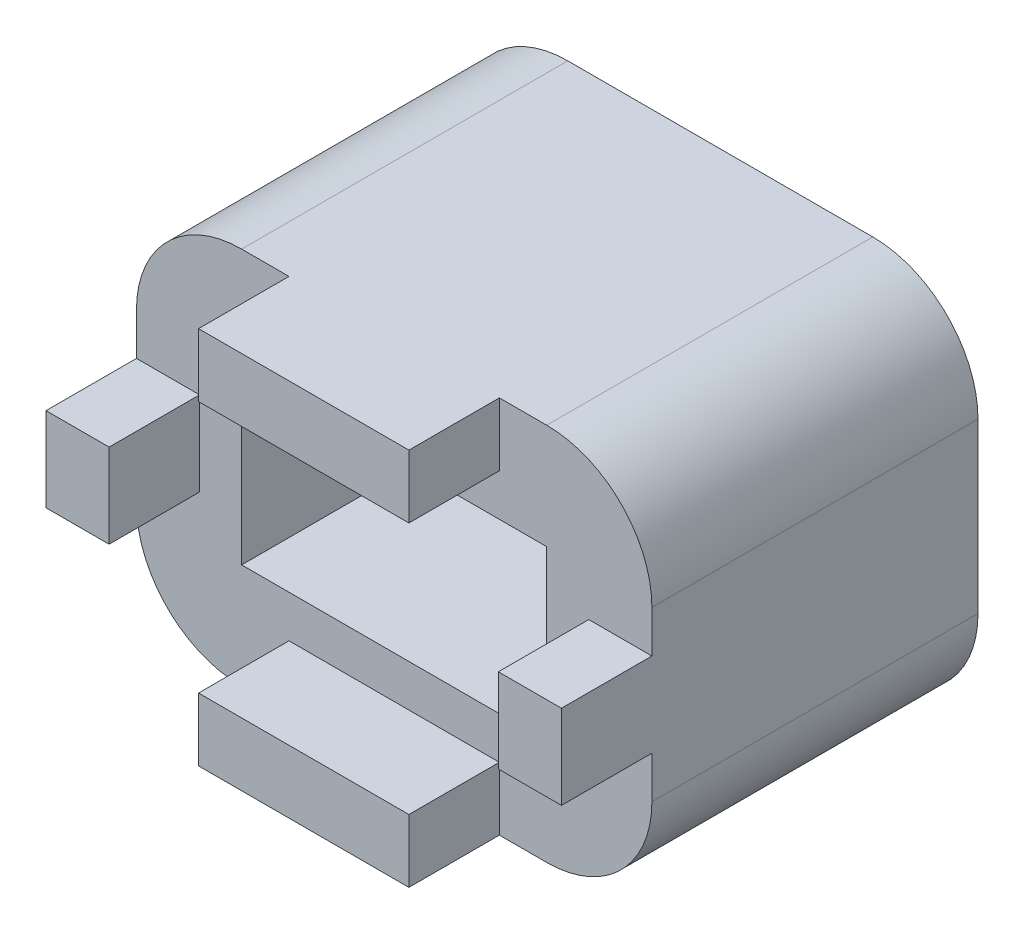
SolidWorks part; units mm, degrees
ref_plane "Front Plane" through (0, 0, 0) normal (0, 0, 1) x (1, 0, 0)
ref_plane "Top Plane" through (0, 0, 0) normal (0, 1, 0) x (1, 0, 0)
ref_plane "Right Plane" through (0, 0, 0) normal (1, 0, 0) x (0, 0, -1)
sketch "Sketch1" plane through (0, 0, 0) normal (0, 0, 1) x (1, 0, 0)
  line L1 (-7.25, -4) -> (7.25, -4)
  line L2 (-7.25, -4) -> (-7.25, 4)
  line L3 (-7.25, 4) -> (7.25, 4)
  line L4 (7.25, -4) -> (7.25, 4)
  line L5 (-7.25, -4) -> (7.25, 4) construction
  line L6 (-7.25, 4) -> (7.25, -4) construction
  line L11 (-12.25, -9) -> (12.25, -9)
  line L12 (-12.25, -9) -> (-12.25, 9)
  line L13 (-12.25, 9) -> (12.25, 9)
  line L14 (12.25, -9) -> (12.25, 9)
  point P0 (0, 0)
  dimension "D1" = 14.5
  dimension "D2" = 8
  dimension "D3" = 5
  dimension "D4" = 5
  dimension "D5" = 5
  dimension "D6" = 5
extrude "Boss-Extrude1" add sketch "Sketch1" along normal blind 15.5
fillet "Fillet1" radius 5 4 edges at (-12.25, 9, 7.75) (12.25, 9, 7.75) (12.25, -9, 7.75) (-12.25, -9, 7.75)
sketch "Sketch3" plane through (0, 0, 15.5) normal (0, 0, 1) x (1, 0, 0)
  line L0 (-7.25, -9) -> (7.25, -9) construction
  line L1 (-5, -9) -> (5, -9)
  line L2 (-5, -9) -> (-5, -6)
  line L3 (-5, -6) -> (5, -6)
  line L4 (5, -9) -> (5, -6)
  line L6 (7.25, 9) -> (-7.25, 9) construction
  line L7 (5, 9) -> (-5, 9)
  line L8 (5, 9) -> (5, 6)
  line L9 (5, 6) -> (-5, 6)
  line L10 (-5, 9) -> (-5, 6)
  line L11 (-12.25, 4) -> (-12.25, -4) construction
  line L12 (-12.25, 2) -> (-9.25, 2)
  line L13 (-12.25, 2) -> (-12.25, -2)
  line L14 (-12.25, -2) -> (-9.25, -2)
  line L15 (-9.25, 2) -> (-9.25, -2)
  line L16 (12.25, -4) -> (12.25, 4) construction
  line L17 (12.25, 2) -> (9.25, 2)
  line L18 (12.25, 2) -> (12.25, -2)
  line L19 (12.25, -2) -> (9.25, -2)
  line L20 (9.25, 2) -> (9.25, -2)
  point P26 (12.25, 0)
  point P27 (9.25, 0)
  point P28 (-9.25, 0)
  point P29 (0, -6)
  point P31 (0, 6)
  dimension "D1" = 10
  dimension "D2" = 10
  dimension "D3" = 4
  dimension "D4" = 4
  dimension "D5" = 3
  dimension "D6" = 3
  dimension "D7" = 3
  dimension "D8" = 3
  dimension "D9" = 3
extrude "Boss-Extrude2" add sketch "Sketch3" along normal blind 4.3
